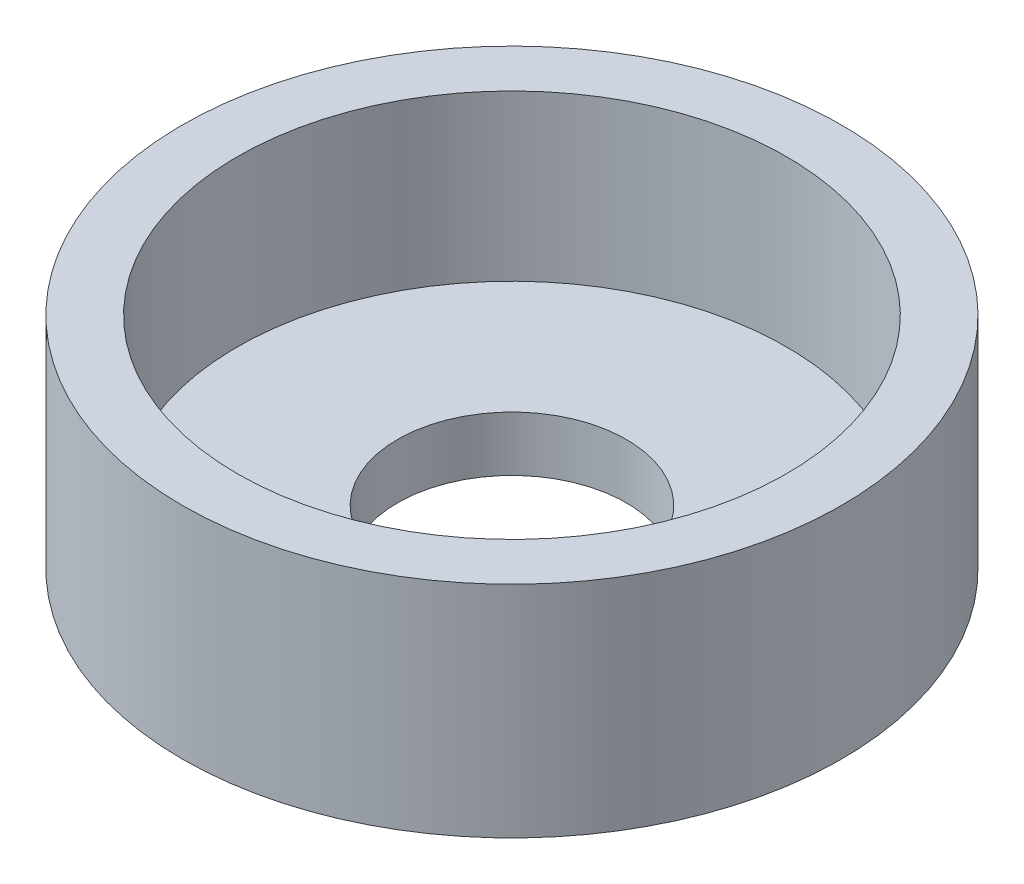
SolidWorks part; units mm, degrees
material "Gray Cast Iron"
ref_plane "Front Plane" through (0, 0, 0) normal (0, 0, 1) x (1, 0, 0)
ref_plane "Top Plane" through (0, 0, 0) normal (0, 1, 0) x (1, 0, 0)
ref_plane "Right Plane" through (0, 0, 0) normal (1, 0, 0) x (0, 0, -1)
sketch "Sketch1" plane through (0, 0, 0) normal (0, 1, 0) x (1, 0, 0)
  circle A0 centre (0, 0) radius 18
  dimension "D1" = 36
extrude "Boss-Extrude1" add sketch "Sketch1" along normal blind 12
sketch "Sketch2" plane through (0, 12, 0) normal (0, 1, 0) x (1, 0, 0)
  circle A0 centre (0, 0) radius 15
  dimension "D1" = 30
extrude "Cut-Extrude1" cut sketch "Sketch2" against normal blind 9
sketch "Sketch3" plane through (0, 3, 0) normal (0, 1, 0) x (1, 0, 0)
  circle A0 centre (0, 0) radius 6.25
  dimension "D1" = 12.5
extrude "Cut-Extrude2" cut sketch "Sketch3" against normal blind 9
